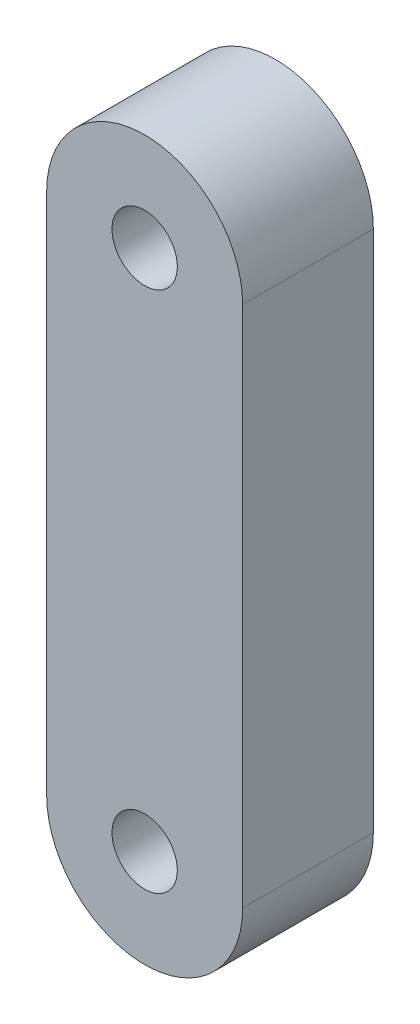
SolidWorks part; units mm, degrees
ref_plane "Plan de face" through (0, 0, 0) normal (0, 0, 1) x (1, 0, 0)
ref_plane "Plan de dessus" through (0, 0, 0) normal (0, 1, 0) x (1, 0, 0)
ref_plane "Plan de droite" through (0, 0, 0) normal (1, 0, 0) x (0, 0, -1)
sketch "Esquisse1" plane through (0, 0, 0) normal (0, 0, 1) x (1, 0, 0)
  line L0 (-1.5, 9) -> (-1.5, 1)
  line L1 (1.5, 9) -> (1.5, 1)
  circle A2 centre (0, 1) radius 0.5
  circle A3 centre (0, 9) radius 0.5
  arc A4 (1.5, 9) -> (-1.5, 9) centre (0, 9) ccw
  arc A5 (-1.5, 1) -> (1.5, 1) centre (0, 1) ccw
  dimension "D1" = 3
extrude "Boss.-Extru.1" add sketch "Esquisse1" along normal blind 2 contours L0 A5 L1 A4 A2 A3
